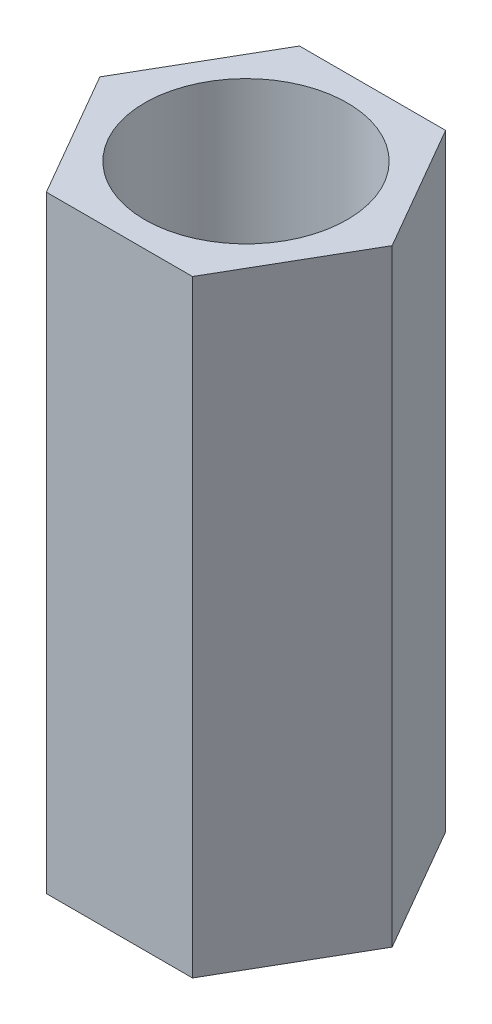
SolidWorks part; units mm, degrees
material "6061 合金"
ref_plane "前视基准面" through (0, 0, 0) normal (0, 0, 1) x (1, 0, 0)
ref_plane "上视基准面" through (0, 0, 0) normal (0, 1, 0) x (1, 0, 0)
ref_plane "右视基准面" through (0, 0, 0) normal (1, 0, 0) x (0, 0, -1)
sketch "草图1" plane through (0, 0, 0) normal (0, 1, 0) x (1, 0, 0)
  line L1 (1.4434, 2.5) -> (-1.4434, 2.5)
  line L2 (-1.4434, 2.5) -> (-2.8868, 0)
  line L3 (-2.8868, 0) -> (-1.4434, -2.5)
  line L4 (-1.4434, -2.5) -> (1.4434, -2.5)
  line L5 (1.4434, -2.5) -> (2.8868, 0)
  line L6 (2.8868, 0) -> (1.4434, 2.5)
  circle A2 centre (0, 0) radius 2
  circle A3 centre (0, 0) radius 2.5 construction
  dimension "D2" = 5
  dimension "D1" = 4
extrude "凸台-拉伸1" add sketch "草图1" along normal blind 12
